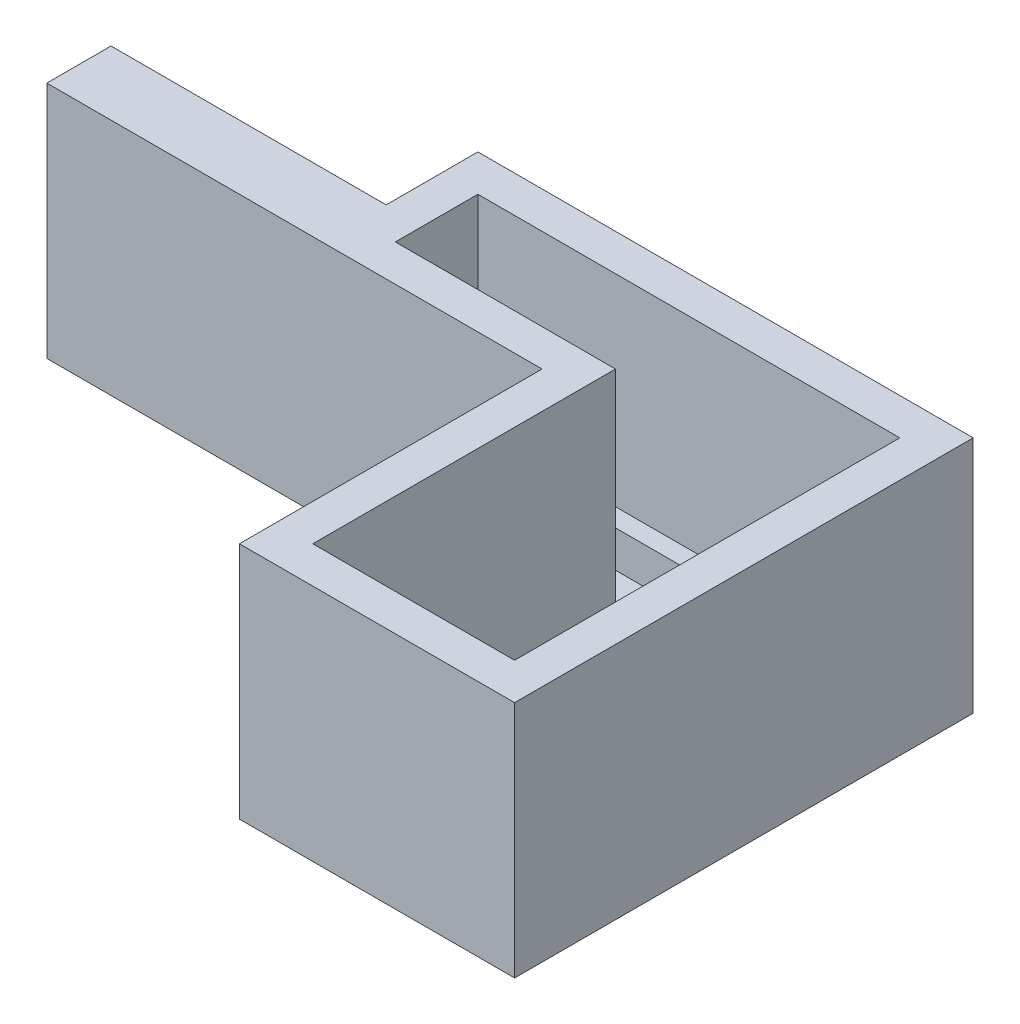
SolidWorks part; units mm, degrees
ref_plane "前视基准面" through (0, 0, 0) normal (0, 0, 1) x (1, 0, 0)
ref_plane "上视基准面" through (0, 0, 0) normal (0, 1, 0) x (1, 0, 0)
ref_plane "右视基准面" through (0, 0, 0) normal (1, 0, 0) x (0, 0, -1)
sketch "草图1" plane through (0, 0, 0) normal (0, 1, 0) x (1, 0, 0)
  line L0 (0, 0) -> (0, 14)
  line L1 (0, 14) -> (-27, 14)
  line L2 (-27, 14) -> (-27, 9)
  line L3 (-27, 9) -> (-42, 9)
  line L4 (-42, 9) -> (-42, 5.5)
  line L5 (-42, 5.5) -> (-15, 5.5)
  line L6 (0, 0) -> (0, -11)
  line L7 (0, -11) -> (-15, -11)
  line L8 (-15, -11) -> (-15, 5.5)
  dimension "D1" = 15
  dimension "D2" = 5
  dimension "D3" = 27
  dimension "D4" = 3.5
  dimension "D5" = 15
  dimension "D6" = 25
extrude "凸台-拉伸1" add sketch "草图1" along normal blind 13
sketch "草图3" plane through (0, 13, 0) normal (0, 1, 0) x (1, 0, 0)
  line L20 (-13, -9) -> (-2, -9)
  line L21 (-13, -9) -> (-2, -9)
  line L22 (-13, 7.5) -> (-13, -9)
  line L24 (-25, 7.5) -> (-13, 7.5)
  line L25 (-2, -9) -> (-2, 12)
  line L26 (-2, 12) -> (-25, 12)
  line L27 (-25, 12) -> (-25, 7.5)
  line L28 (-13, 7.5) -> (-13, -9)
  line L30 (-25, 7.5) -> (-13, 7.5)
  line L31 (-2, -9) -> (-2, 12)
  line L32 (-2, 12) -> (-25, 12)
  line L33 (-25, 12) -> (-25, 7.5)
  dimension "D1" = 2
extrude "切除-拉伸1" cut sketch "草图3" against normal offset from surface (11 mm away) 2 up to face at (-21, 0, -4.375)
sketch "草图5" plane through (0, 2, 0) normal (0, 1, 0) x (1, 0, 0)
  line L0 (-27, 9) -> (-42, 9) construction
  line L1 (-23, 11) -> (-9, 11)
  line L2 (-23, 11) -> (-23, 9)
  line L3 (-23, 9) -> (-9, 9)
  line L4 (-9, 11) -> (-9, 9)
  line L5 (-25, 7.5) -> (-25, 12) construction
  line L7 (-2, 12) -> (-25, 12) construction
  dimension "D1" = 2
  dimension "D2" = 1
  dimension "D3" = 14
extrude "切除-拉伸2" cut sketch "草图5" against normal blind 10
sketch "草图8" plane through (0, 2, 0) normal (0, 1, 0) x (1, 0, 0)
  line L1 (-2, 12) -> (-25, 12) construction
  line L2 (-13, -9) -> (-2, -9) construction
  line L3 (-7.5, -9) -> (-7.5, 15.0604) construction
  circle A0 centre (-7.5, 8) radius 1.65
  circle A1 centre (-7.5, -5) radius 1.65
  dimension "D1" = 3.3
  dimension "D3" = 4
  dimension "D4" = 3.3
  dimension "D5" = 4
  dimension "D7" = 13
extrude "切除-拉伸5" cut sketch "草图8" against normal blind 20
